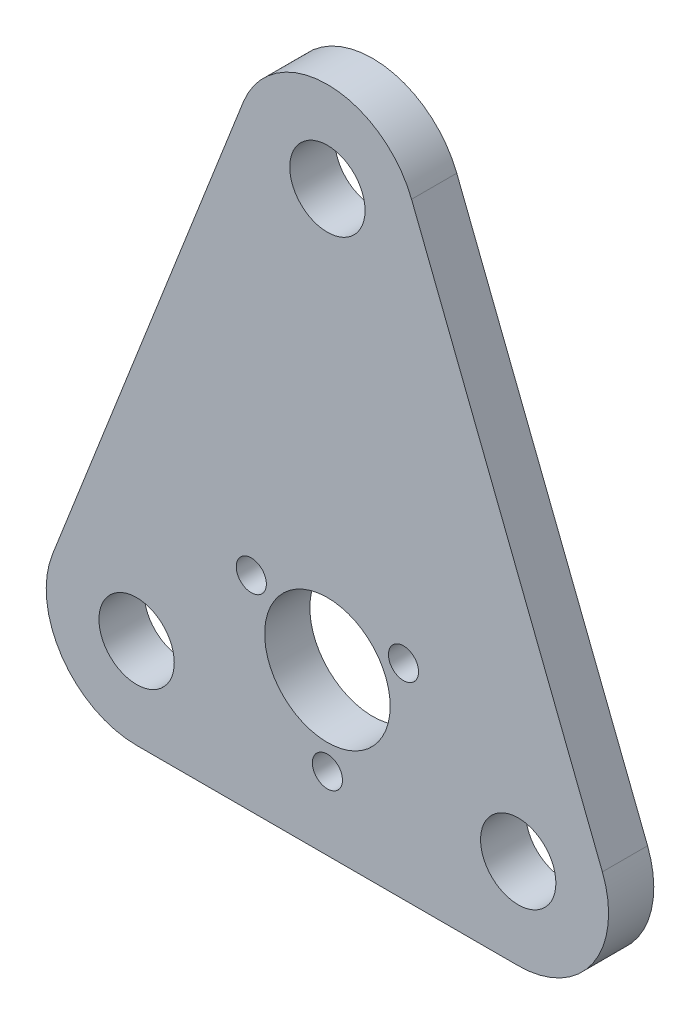
SolidWorks part; units mm, degrees
material "AISI 304"
ref_plane "Plano frontal" through (0, 0, 0) normal (0, 0, 1) x (1, 0, 0)
ref_plane "Plano superior" through (0, 0, 0) normal (0, 1, 0) x (1, 0, 0)
ref_plane "Plano direito" through (0, 0, 0) normal (1, 0, 0) x (0, 0, -1)
sketch "Esboço1" plane through (0, 0, 0) normal (0, 0, 1) x (1, 0, 0)
  line L0 (0, 70.941) -> (0, -84.8195) construction
  line L1 (-107.5365, 0) -> (134.9856, 0) construction
  line L2 (-30.3109, 17.5) -> (0, 0) construction
  line L3 (0, 0) -> (15.1554, 8.75)
  line L4 (15.1554, 8.75) -> (43.9221, 25.3584) construction
  line L5 (-16.7598, 89.5657) -> (-54.7598, -7.4343)
  line L6 (16.7598, 89.5657) -> (54.7598, -7.4343)
  line L7 (38, -32) -> (-38, -32)
  circle A0 centre (0, 0) radius 12.5
  circle A1 centre (0, 83) radius 7.5
  circle A2 centre (38, -14) radius 7.5
  circle A3 centre (-38, -14) radius 7.5
  circle A4 centre (0, -17.5) radius 3
  circle A5 centre (15.1554, 8.75) radius 3
  circle A6 centre (-15.1554, 8.75) radius 3
  circle A7 centre (0, 0) radius 17.5 construction
  arc A8 (-54.7598, -7.4343) -> (-38, -32) centre (-38, -14) ccw
  arc A9 (38, -32) -> (54.7598, -7.4343) centre (38, -14) ccw
  arc A10 (16.7598, 89.5657) -> (-16.7598, 89.5657) centre (0, 83) ccw
  point P22 (-15.1554, 8.75)
  dimension "D1" = 30
  dimension "D2" = 25
  dimension "D3" = 6
  dimension "D4" = 6
  dimension "D5" = 15
  dimension "D6" = 15
  dimension "D7" = 76
  dimension "D8" = 35
  dimension "D9" = 36
  dimension "D10" = 32
  dimension "D11" = 115
extrude "Ressalto-extrusão2" add sketch "Esboço1" along normal mid plane 9
